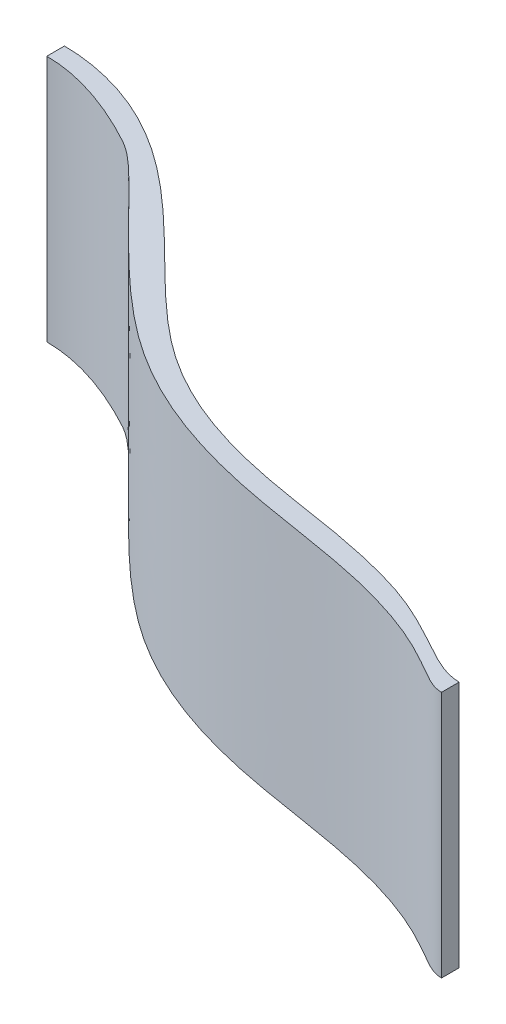
SolidWorks part; units mm, degrees
ref_plane "前视基准面" through (0, 0, 0) normal (0, 0, 1) x (1, 0, 0)
ref_plane "上视基准面" through (0, 0, 0) normal (0, 1, 0) x (1, 0, 0)
ref_plane "右视基准面" through (0, 0, 0) normal (1, 0, 0) x (0, 0, -1)
other "Configuration Table"
sketch "草图1" plane through (0, 0, 0) normal (0, 1, 0) x (1, 0, 0)
  line L0 (0, 0) -> (0, -600)
  line L1 (0, -600) -> (1270, -600)
  line L4 (31.0073, 0) -> (-30.2708, 0) construction
  line L6 (1276.9062, -600) -> (1242.3537, -600) construction
  line L7 (0, 0) -> (0, 30)
  line L9 (1270, -600) -> (1270, -570)
  line L11 (46.6908, 30) -> (-46.6908, 30) construction
  line L12 (1361.0184, -570) -> (1178.9816, -570) construction
  spline S0 degree 3 poles (0, 0) (63.9163, 0) (150.2107, -38.8707) (245.1999, -90.9747) (512.5613, -420.5403) (858.8148, -476.0373) (1192.6141, -530.3029) (1228.9453, -600) (1270, -600) knots 0 0 0 0 0.117725 0.147166 0.294405 0.459334 0.529893 1 1 1 1
  spline S1 degree 3 poles (0, 30) (42.1725, 30) (267.8854, -19.4338) (486.4697, -345.7128) (745.0831, -425.5262) (948.3219, -455.0225) (1150.3776, -495.7445) (1223.3164, -570) (1270, -570) knots 0 0 0 0 0.084774 0.417203 0.65115 0.689341 0.79911 1 1 1 1
  point P9 (1092.2009, -448.652)
  point P11 (1160.0233, -509.7821)
  point P18 (1084.2408, -489.8509)
  point P20 (890.9229, -446.7814)
  dimension "D3" = 30
  dimension "D1" = 600
  dimension "D2" = 1270
extrude "凸台-拉伸1" add sketch "草图1" along normal blind 420 contours S1 L7 S0 L9
